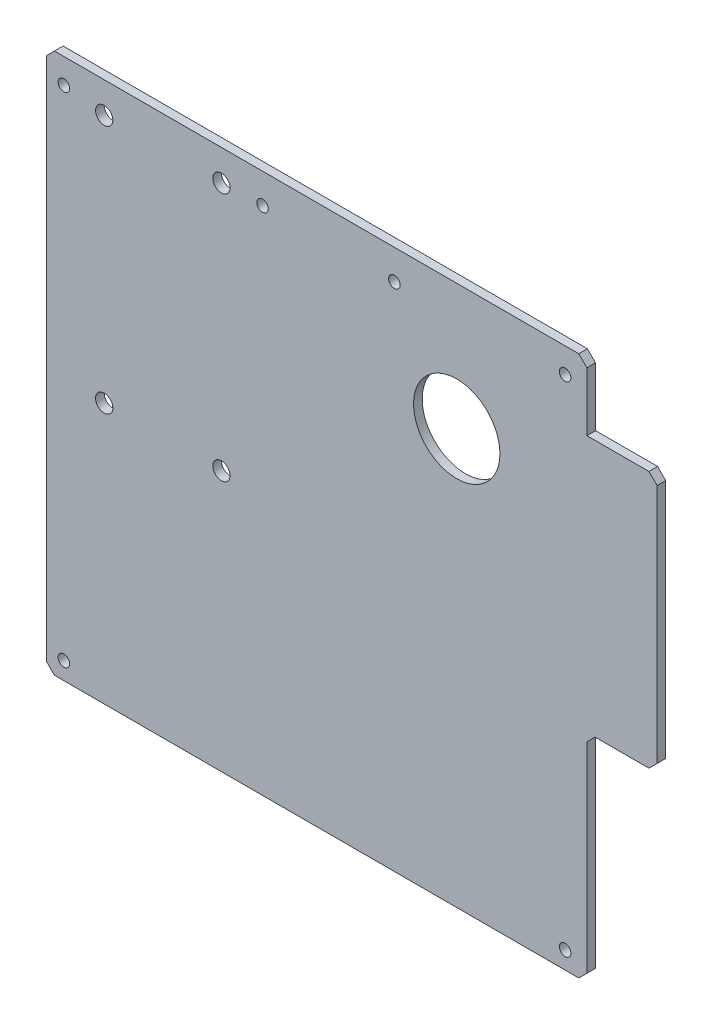
SolidWorks part; units mm, degrees
material "Brass"
ref_plane "Front Plane" through (0, 0, 0) normal (0, 0, 1) x (1, 0, 0)
ref_plane "Top Plane" through (0, 0, 0) normal (0, 1, 0) x (1, 0, 0)
ref_plane "Right Plane" through (0, 0, 0) normal (1, 0, 0) x (0, 0, -1)
sketch "Sketch1" plane through (0, 0, 0) normal (0, 0, 1) x (1, 0, 0)
  line L0 (89.4531, 4.337) -> (-1.6432, 4.337)
  line L1 (-1.6432, 4.337) -> (-3.0574, 2.9228)
  line L2 (-3.0574, 2.9228) -> (-3.0574, -88.1735)
  line L3 (-3.0574, -88.1735) -> (-1.6432, -89.5877)
  line L4 (-1.6432, -89.5877) -> (89.4531, -89.5877)
  line L5 (89.4531, -89.5877) -> (90.8673, -88.1735)
  line L6 (90.8673, -88.1735) -> (90.8673, -53.3417)
  line L7 (90.8673, -53.3417) -> (92.2815, -51.9274)
  line L8 (92.2815, -51.9274) -> (101.6433, -51.9274)
  line L9 (101.6433, -51.9274) -> (103.0576, -50.5132)
  line L10 (103.0576, -50.5132) -> (103.0576, -8.6929)
  line L11 (103.0576, -8.6929) -> (101.6433, -7.2787)
  line L12 (101.6433, -7.2787) -> (90.8673, -7.2787)
  line L13 (90.8673, -7.2787) -> (90.8673, 2.9228)
  line L14 (90.8673, 2.9228) -> (89.4531, 4.337)
  circle A1 centre (7.0029, -1.0185) radius 1.5
  circle A2 centre (27.3718, -1.0185) radius 1.5
  circle A3 centre (34.509, -0.8681) radius 1
  circle A4 centre (57.4135, -0.8681) radius 1
  circle A5 centre (87.0794, 0.0031) radius 1
  circle A6 centre (68.2507, -17.5589) radius 7.5025
  circle A7 centre (7.0029, -44.3172) radius 1.5
  circle A8 centre (27.3718, -44.3172) radius 1.5
  circle A9 centre (0, -86.5552) radius 1
  circle A10 centre (87.0794, -86.5552) radius 1
  circle A11 centre (0, 0) radius 1
  dimension "D20" = 2
  dimension "D21" = 3
  dimension "D22" = 15.005
  dimension "D1" = 93.9248
  dimension "D2" = 93.9248
  dimension "D3" = 37.6603
  dimension "D4" = 11.6158
  dimension "D5" = 3.7879
  dimension "D6" = 3.0574
  dimension "D7" = 10.0603
  dimension "D8" = 20.3689
  dimension "D9" = 43.2988
  dimension "D10" = 5.3555
  dimension "D11" = 4.3339
  dimension "D12" = 5.2052
  dimension "D13" = 22.9045
  dimension "D14" = 7.1372
  dimension "D15" = 4.337
  dimension "D16" = 3.0325
  dimension "D17" = 12.1902
  dimension "D18" = 21.8959
  dimension "D19" = 10.8372
  dimension "D23" = 45
  dimension "D24" = 2
  dimension "D25" = 2
  dimension "D26" = 45
  dimension "D27" = 45
  dimension "D28" = 45
  dimension "D29" = 45
  dimension "D30" = 45
  dimension "D31" = 45
extrude "Boss-Extrude2" add sketch "Sketch1" along normal blind 1.5 separate body
